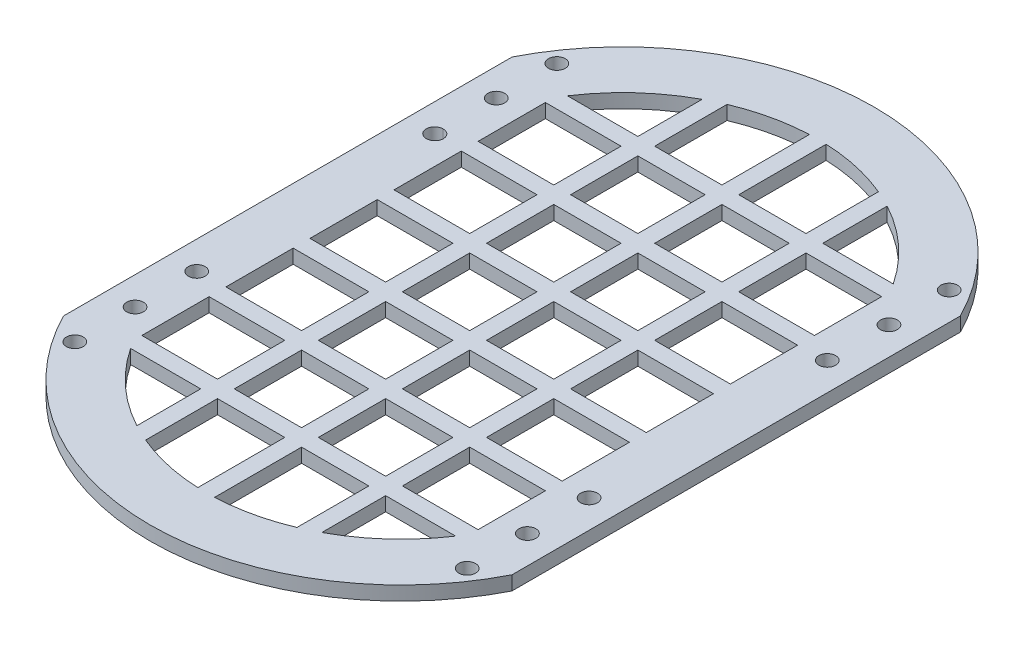
SolidWorks part; units mm, degrees
ref_plane "Front Plane" through (0, 0, 0) normal (0, 0, 1) x (1, 0, 0)
ref_plane "Top Plane" through (0, 0, 0) normal (0, 1, 0) x (1, 0, 0)
ref_plane "Right Plane" through (0, 0, 0) normal (1, 0, 0) x (0, 0, -1)
sketch "Sketch1" plane through (0, 0, 0) normal (0, 1, 0) x (1, 0, 0)
  line L0 (0, 80) -> (191.8529, 80) construction
  line L6 (0, 0) -> (0, 160)
  line L8 (160, 0) -> (160, 160)
  arc A2 (0, 160) -> (160, 160) centre (80, 119.5198) cw
  arc A3 (0, 160) -> (160, 160) centre (80, 160) cw construction
  arc A4 (0, 0) -> (160, 0) centre (80, 40.4802) ccw
  dimension "D3" = 89.6585
  dimension "D1" = 160
  dimension "D2" = 160
extrude "Boss-Extrude1" add sketch "Sketch1" along normal blind 5
sketch "Sketch4" plane through (0, 5, 0) normal (0, 1, 0) x (1, 0, 0)
  line L5 (140, 5.0923) -> (140, 154.9077)
  line L6 (20, 154.9077) -> (20, 5.0923)
  line L7 (50, 211.0646) -> (50, -56.0833)
  line L8 (80, 211.0646) -> (80, -56.0833)
  line L11 (110, 211.0646) -> (110, -56.0833)
  line L15 (-45.0808, 4.9077) -> (199.29, 4.9077)
  line L16 (-45.0808, 124.9077) -> (199.29, 124.9077)
  line L17 (-45.0808, 94.9077) -> (199.29, 94.9077)
  line L18 (-45.0808, 64.9077) -> (199.29, 64.9077)
  line L19 (-45.0808, 34.9077) -> (199.29, 34.9077)
  line L20 (-45.0808, 154.9077) -> (199.29, 154.9077)
  line L21 (-45.0808, 151.9077) -> (199.29, 151.9077)
  line L22 (47, 211.0646) -> (47, -56.0833)
  line L23 (77, 211.0646) -> (77, -56.0833)
  line L24 (107, 211.0646) -> (107, -56.0833)
  line L25 (-45.0808, 157.9077) -> (199.29, 157.9077)
  line L26 (53, 211.0646) -> (53, -56.0833)
  line L27 (83, 211.0646) -> (83, -56.0833)
  line L28 (113, 211.0646) -> (113, -56.0833)
  line L29 (-45.0808, 121.9077) -> (199.29, 121.9077)
  line L30 (-45.0808, 91.9077) -> (199.29, 91.9077)
  line L31 (-45.0808, 61.9077) -> (199.29, 61.9077)
  line L32 (-45.0808, 31.9077) -> (199.29, 31.9077)
  line L33 (-45.0808, 1.9077) -> (199.29, 1.9077)
  line L34 (-45.0808, 127.9077) -> (199.29, 127.9077)
  line L35 (-45.0808, 97.9077) -> (199.29, 97.9077)
  line L36 (-45.0808, 67.9077) -> (199.29, 67.9077)
  line L37 (-45.0808, 37.9077) -> (199.29, 37.9077)
  line L38 (-45.0808, 7.9077) -> (199.29, 7.9077)
  arc A0 (140, 154.9077) -> (20, 154.9077) centre (80, 119.5198) ccw
  arc A1 (20, 5.0923) -> (140, 5.0923) centre (80, 40.4802) ccw
  dimension "D1" = 30
  dimension "D2" = 3
  dimension "D3" = 3
  dimension "D4" = 3
  dimension "D6" = 3
  dimension "D7" = 3
extrude "Cut-Extrude1" cut sketch "Sketch4" against normal blind 6 contours L22 A0 L25 | L23 A0 L26 L25 | L24 A0 L27 L25 | L25 A0 L28 | L28 L34 L5 L21 | L27 L34 L24 L21 | L26 L34 L23 L21 | L6 L34 L22 L21 | L6 L35 L22 L29 | L26 L35 L23 L29 | L27 L35 L24 L29 | L28 L35 L5 L29 | L28 L36 L5 L30 | L27 L36 L24 L30 | L26 L36 L23 L30 | L6 L36 L22 L30 | L6 L37 L22 L31 | L26 L37 L23 L31 | L27 L37 L24 L31 | L28 L37 L5 L31 | L28 L38 L5 L32 | L27 L38 L24 L32 | L26 L38 L23 L32 | L6 L38 L22 L32 | L33 A1 L22 | L26 A1 L23 L33 | L27 A1 L24 L33 | L28 A1 L33
sketch "Sketch5" plane through (0, 5, 0) normal (0, 1, 0) x (1, 0, 0)
  line L0 (0, 80) -> (201.3848, 80) construction
  line L1 (0, 160) -> (0, 0) construction
  line L2 (80, 209.1783) -> (80, -99.5859) construction
  circle A0 centre (10, 37.5) radius 3
  arc A1 (160, 160) -> (0, 160) centre (80, 119.5198) ccw construction
  circle A2 centre (150, 37.5) radius 3
  circle A3 centre (150, 122.5) radius 3
  circle A4 centre (10, 122.5) radius 3
  dimension "D1" = 37.5
  dimension "D3" = 6
  dimension "D2" = 10
extrude "Cut-Extrude2" cut sketch "Sketch5" against normal blind 44
sketch "Sketch6" plane through (0, 5, 0) normal (0, 1, 0) x (1, 0, 0)
  line L0 (10, 46.3052) -> (10, 3.8665) construction
  line L1 (150, 150.6243) -> (150, -5.6642) construction
  line L2 (155.6387, 37.5) -> (145.0603, 37.5) construction
  circle A0 centre (9.8857, 144.5) radius 3
  circle A1 centre (9.8857, 122.5) radius 3
  circle A2 centre (10, 122.5) radius 3 construction
  circle A3 centre (150, 122.5) radius 3 construction
  circle A4 centre (10, 37.5) radius 3 construction
  circle A5 centre (150, 122.5) radius 3 construction
  circle A6 centre (10, 37.5) radius 3 construction
  circle A7 centre (10, 15.5) radius 3
  circle A10 centre (150, 144.5) radius 3
  circle A11 centre (150, 15.5) radius 3
  dimension "D1" = 6
  dimension "D2" = 6
  dimension "D5" = 22
  dimension "D6" = 6
  dimension "D7" = 6
  dimension "D10" = 6
  dimension "D3" = 0
  dimension "D4" = 22
  dimension "D8" = 22
  dimension "D9" = 22
extrude "Cut-Extrude3" cut sketch "Sketch6" against normal blind 70
sketch "Sketch7" plane through (0, 5, 0) normal (0, 1, 0) x (1, 0, 0)
  line L0 (160, 0) -> (160, 160) construction
  line L1 (160, 0) -> (160, 160) construction
  line L2 (0, 80) -> (221.9195, 80) construction
  line L3 (0, 160) -> (0, 0) construction
  circle A0 centre (10, 166) radius 3
  circle A1 centre (150, 166) radius 3
  circle A2 centre (150, -6) radius 3
  circle A3 centre (10, -6) radius 3
  dimension "D3" = 6
  dimension "D4" = 6
  dimension "D1" = 10
  dimension "D2" = 6
  dimension "D5" = 10
  dimension "D6" = 6
extrude "Cut-Extrude4" cut sketch "Sketch7" against normal blind 95
